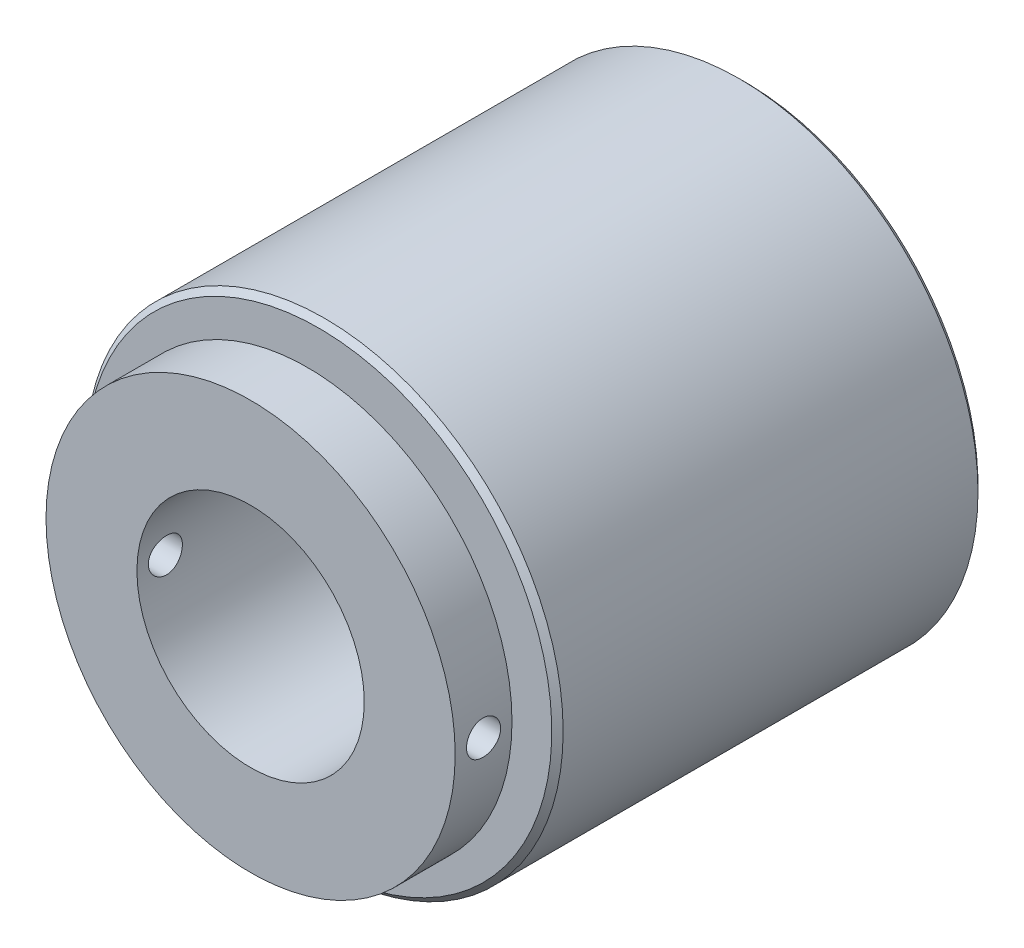
SolidWorks part; units mm, degrees
ref_plane "前视基准面" through (0, 0, 0) normal (0, 0, 1) x (1, 0, 0)
ref_plane "上视基准面" through (0, 0, 0) normal (0, 1, 0) x (1, 0, 0)
ref_plane "右视基准面" through (0, 0, 0) normal (1, 0, 0) x (0, 0, -1)
sketch "草图1" plane through (0, 0, 0) normal (0, 0, 1) x (1, 0, 0)
  circle A0 centre (0, 0) radius 18
  circle A1 centre (0, 0) radius 10
extrude "凸台-拉伸1" add sketch "草图1" along normal blind 5
sketch "草图2" plane through (0, 0, 0) normal (1, 0, 0) x (0, 0, -1)
  line L0 (-5, 0) -> (0, 0) construction
  line L1 (-5, 18) -> (-5, -18) construction
  circle A0 centre (-2.5, 0) radius 1.5
extrude "切除-拉伸1" cut sketch "草图2" against normal blind 19 and the other way blind 35
sketch "草图3" plane through (0, 0, 0) normal (0, 0, -1) x (-1, 0, 0)
  circle A0 centre (0, 0) radius 10
  circle A1 centre (0, 0) radius 10.4159
extrude "凸台-拉伸2" add sketch "草图3" along normal blind 1
sketch "草图4" plane through (0, 0, -1) normal (0, 0, -1) x (-1, 0, 0)
  circle A0 centre (0, 0) radius 10
  circle A1 centre (0, 0) radius 21
extrude "凸台-拉伸3" add sketch "草图4" along normal blind 37.5 contours A1 | A0
chamfer "倒角1" distance 0.5 angle 45 2 edges at (-21, 0, -38.5) (-21, 0, -1)
sketch "草图5" plane through (0, 0, -38.5) normal (0, 0, -1) x (-1, 0, 0)
  line L0 (0, -18) -> (0, 18)
  line L1 (3, 18) -> (-3, 18)
  circle A0 centre (-3, 18) radius 1
  circle A1 centre (3, 18) radius 1
  circle A2 centre (-3, -18) radius 1
  circle A3 centre (3, -18) radius 1
  point P4 (0, 0)
  point P8 (0, 18)
extrude "切除-拉伸2" cut sketch "草图5" against normal blind 1 contours A3 | A2 | A0 | A1
